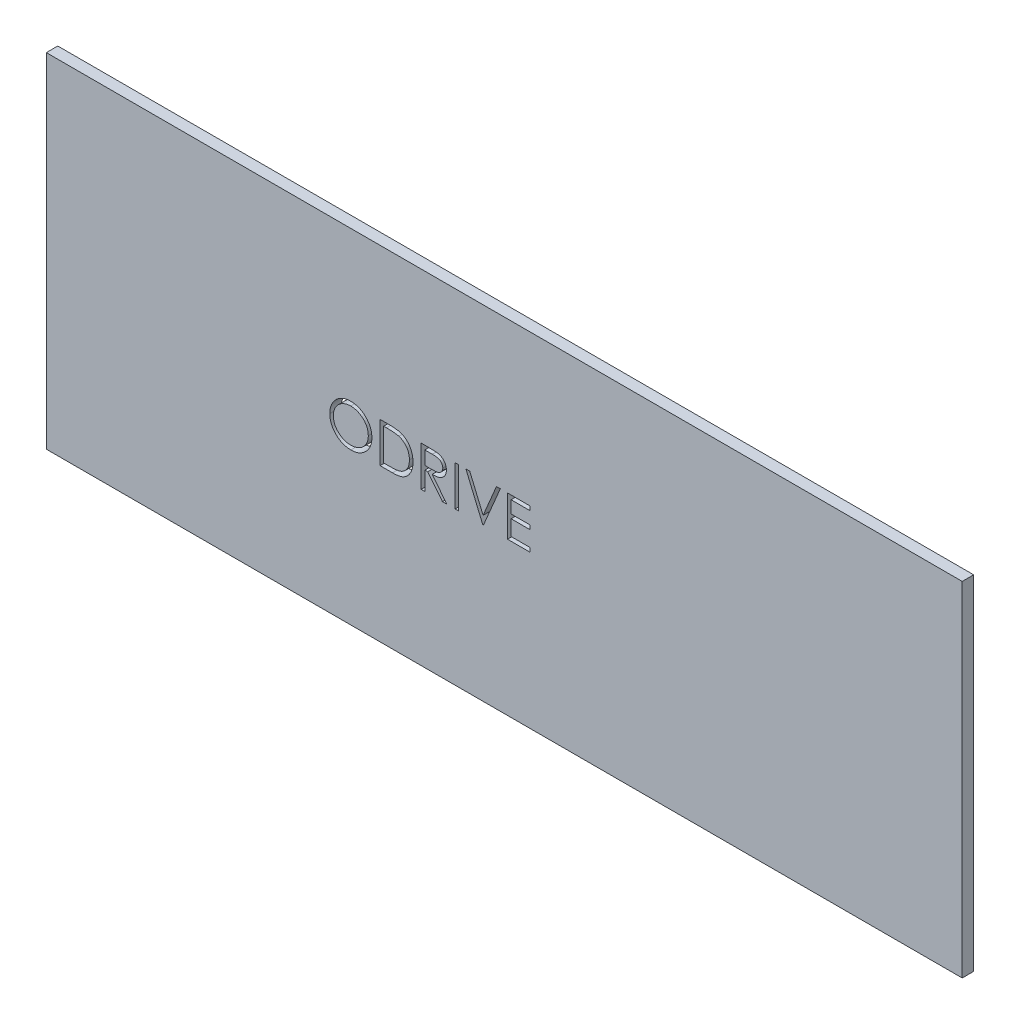
SolidWorks part; units mm, degrees
ref_plane "Front Plane" through (0, 0, 0) normal (0, 0, 1) x (1, 0, 0)
ref_plane "Top Plane" through (0, 0, 0) normal (0, 1, 0) x (1, 0, 0)
ref_plane "Right Plane" through (0, 0, 0) normal (1, 0, 0) x (0, 0, -1)
sketch "Sketch1" plane through (0, 0, 0) normal (0, 0, 1) x (1, 0, 0)
  line L1 (-54.4024, -10.4324) -> (25.5976, -10.4324)
  line L2 (-54.4024, -10.4324) -> (-54.4024, -40.4324)
  line L3 (-54.4024, -40.4324) -> (25.5976, -40.4324)
  line L4 (25.5976, -10.4324) -> (25.5976, -40.4324)
  dimension "D1" = 80
  dimension "D2" = 30
extrude "Boss-Extrude1" add sketch "Sketch1" along normal blind 1
sketch "Sketch2" plane through (0, 0, 1) normal (0, 0, 1) x (1, 0, 0)
  text T0 "ODRIVE"
extrude "Cut-Extrude2" cut sketch "Sketch2" against normal through all
